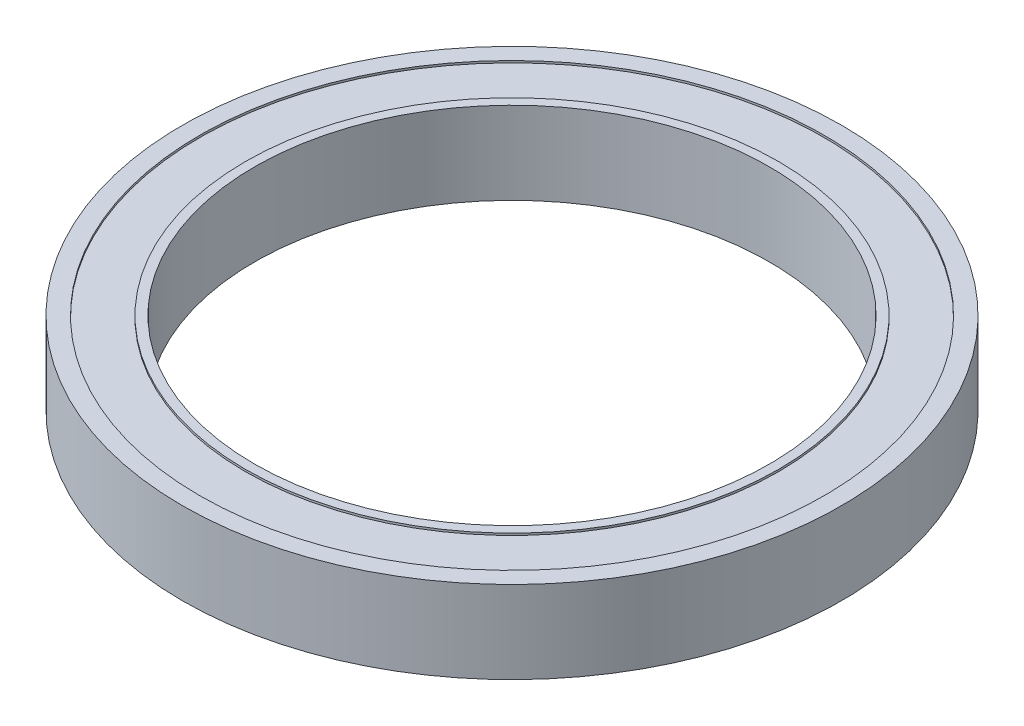
SolidWorks part; units mm, degrees
ref_plane "前视基准面" through (0, 0, 0) normal (0, 0, 1) x (1, 0, 0)
ref_plane "上视基准面" through (0, 0, 0) normal (0, 1, 0) x (1, 0, 0)
ref_plane "右视基准面" through (0, 0, 0) normal (1, 0, 0) x (0, 0, -1)
other "Configuration Table"
sketch "草图1" plane through (0, 0, 0) normal (0, 1, 0) x (1, 0, 0)
  circle A0 centre (0, 0) radius 16
  circle A1 centre (0, 0) radius 12.5
extrude "凸台-拉伸1" add sketch "草图1" along normal mid plane 4
sketch "草图2" plane through (0, 2, 0) normal (0, 1, 0) x (1, 0, 0)
  circle A0 centre (0, 0) radius 15.1588
  circle A1 centre (0, 0) radius 12.9432
extrude "切除-拉伸1" cut sketch "草图2" against normal blind 0.1
mirror "镜向1" about plane through (0, 0, 0) normal (0, 1, 0) of "切除-拉伸1"
